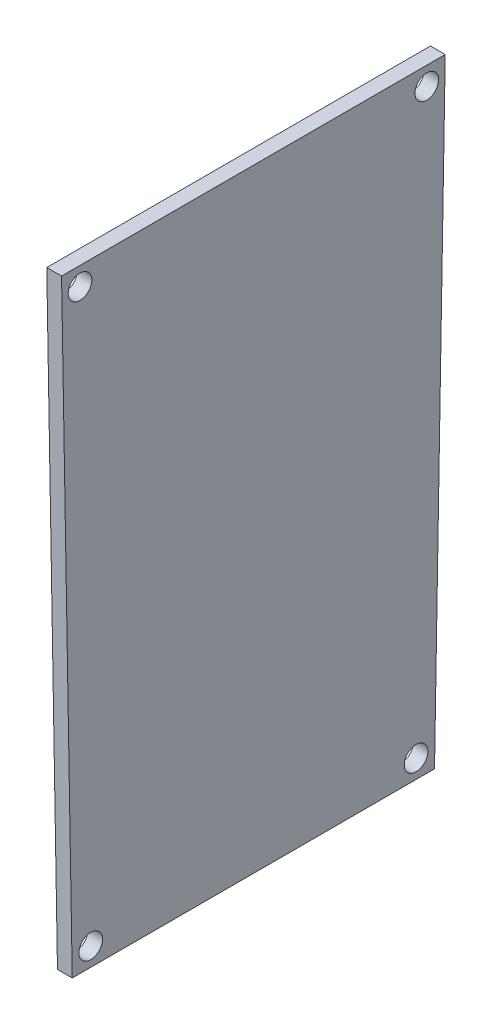
SolidWorks part; units mm, degrees
ref_plane "Front Plane" through (0, 0, 0) normal (0, 0, 1) x (1, 0, 0)
ref_plane "Top Plane" through (0, 0, 0) normal (0, 1, 0) x (1, 0, 0)
ref_plane "Right Plane" through (0, 0, 0) normal (1, 0, 0) x (0, 0, -1)
ref_plane "Plane1" through (52.7733, 0, 0) normal (1, 0, 0) x (0, 0, -1)
sketch "Sketch1" plane through (52.7733, 0, 0) normal (1, 0, 0) x (0, 0, -1)
  line L0 (-92.5053, 27.0324) -> (-43.4739, 27.0324) construction
  line L1 (-93.9541, 110.0324) -> (-92.5053, 27.0324) construction
  line L2 (-43.4739, 27.0324) -> (-42.0251, 110.0324) construction
  line L3 (-42.0251, 110.0324) -> (-93.9541, 110.0324) construction
  line L4 (-92.5053, 27.0324) -> (-43.4739, 27.0324)
  line L5 (-93.9541, 110.0324) -> (-92.5053, 27.0324)
  line L6 (-43.4739, 27.0324) -> (-42.0251, 110.0324)
  line L7 (-42.0251, 110.0324) -> (-93.9541, 110.0324)
ref_plane "Plane2" through (52.7733, 0, 0) normal (1, 0, 0) x (0, 0, -1)
sketch "Sketch2" plane through (52.7733, 0, 0) normal (1, 0, 0) x (0, 0, -1)
  circle A0 centre (-44.5251, 107.5324) radius 1.6 construction
  circle A1 centre (-91.4541, 107.5324) radius 1.6 construction
  circle A2 centre (-45.9739, 29.5324) radius 1.6 construction
  circle A3 centre (-90.0053, 29.5324) radius 1.6 construction
  circle A4 centre (-44.5251, 107.5324) radius 1.6
  circle A5 centre (-91.4541, 107.5324) radius 1.6
  circle A6 centre (-45.9739, 29.5324) radius 1.6
  circle A7 centre (-90.0053, 29.5324) radius 1.6
extrude "Boss-Extrude1" add sketch "Sketch1" against normal blind 2
extrude "Cut-Extrude4" cut sketch "Sketch2" against normal blind 2
